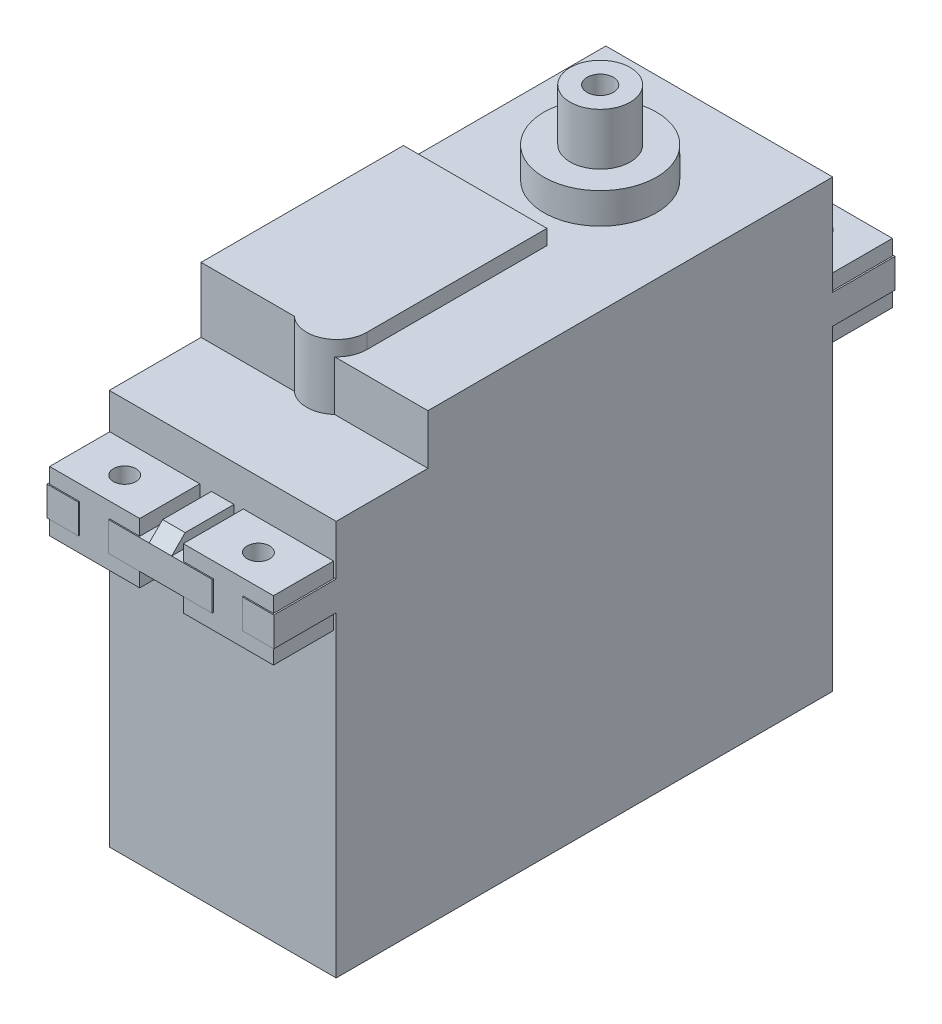
SolidWorks part; units mm, degrees
ref_plane "Front Plane" through (0, 0, 0) normal (0, 0, 1) x (1, 0, 0)
ref_plane "Top Plane" through (0, 0, 0) normal (0, 1, 0) x (1, 0, 0)
ref_plane "Right Plane" through (0, 0, 0) normal (1, 0, 0) x (0, 0, -1)
sketch "Sketch1" plane through (0, 0, 0) normal (1, 0, 0) x (0, 0, -1)
  line L0 (0, 0) -> (66.1, 0)
  line L1 (66.1, 0) -> (66.1, 42.1)
  line L2 (66.1, 42.1) -> (74.4, 42.1)
  line L3 (74.4, 42.1) -> (74.4, 46)
  line L4 (74.4, 46) -> (66.1, 46)
  line L5 (66.1, 46) -> (66.1, 59.3)
  line L6 (66.1, 59.3) -> (12.2136, 59.3)
  line L7 (12.2136, 59.3) -> (12.2136, 52.65)
  line L8 (12.2136, 52.65) -> (0, 52.65)
  line L9 (0, 52.65) -> (0, 46)
  line L10 (0, 46) -> (-8.3, 46)
  line L11 (-8.3, 46) -> (-8.3, 42.1)
  line L12 (-8.3, 42.1) -> (0, 42.1)
  line L13 (0, 42.1) -> (0, 0)
  dimension "D1" = 13.3
extrude "Boss-Extrude1" add sketch "Sketch1" along normal blind 30.2
sketch "Sketch9" plane through (0, 46, 0) normal (0, 1, 0) x (1, 0, 0)
  line L0 (15.1, 74.4) -> (15.1, -8.3) construction
  line L1 (30.2, 74.4) -> (0, 74.4) construction
  line L2 (30.2, -8.3) -> (0, -8.3) construction
  line L4 (22, 74.4) -> (22, 72.1375)
  line L5 (6.2, 74.4) -> (4.2, 74.4)
  line L6 (4.2, 74.4) -> (4.2, 72.1375)
  line L7 (6.2, 74.4) -> (8.2, 74.4)
  line L8 (8.2, 74.4) -> (8.2, 72.1375)
  line L9 (24, 74.4) -> (22, 74.4)
  line L10 (26, 74.4) -> (26, 72.1375)
  line L11 (24, 74.4) -> (26, 74.4)
  line L12 (0, 74.4) -> (0, 33.05) construction
  line L13 (0, 66.1) -> (0, 12.2136) construction
  line L14 (0, 33.05) -> (30.2, 33.05) construction
  line L15 (30.2, 66.1) -> (30.2, 12.2136) construction
  line L17 (24, -8.3) -> (26, -8.3)
  line L18 (26, -8.3) -> (26, -6.0375)
  line L19 (24, -8.3) -> (22, -8.3)
  line L20 (8.2, -8.3) -> (8.2, -6.0375)
  line L21 (6.2, -8.3) -> (8.2, -8.3)
  line L22 (4.2, -8.3) -> (4.2, -6.0375)
  line L23 (6.2, -8.3) -> (4.2, -8.3)
  line L24 (22, -8.3) -> (22, -6.0375)
  arc A0 (4.2, 72.1375) -> (8.2, 72.1375) centre (6.2, 70.25) ccw
  arc A1 (26, 72.1375) -> (22, 72.1375) centre (24, 70.25) cw
  arc A2 (26, -6.0375) -> (22, -6.0375) centre (24, -4.15) ccw
  arc A3 (4.2, -6.0375) -> (8.2, -6.0375) centre (6.2, -4.15) cw
extrude "Cut-Extrude3" cut sketch "Sketch9" against normal blind 6.9
sketch "Sketch10" plane through (0, 59.3, 0) normal (0, 1, 0) x (1, 0, 0)
  line L0 (6.2, 70.25) -> (6.2, 50.25) construction
  line L1 (6.2, 50.25) -> (17.2217, 50.25) construction
  line L2 (15.1, 74.4) -> (15.1, 50.25) construction
  line L3 (22, 74.4) -> (8.2, 74.4) construction
  circle A0 centre (15.1, 50.25) radius 7.5
extrude "Boss-Extrude6" add sketch "Sketch10" along normal blind 4.1
sketch "Sketch11" plane through (0, 63.4, 0) normal (0, 1, 0) x (1, 0, 0)
  circle A0 centre (15.1, 50.25) radius 4
  dimension "D1" = 8
extrude "Boss-Extrude7" add sketch "Sketch11" along normal blind 6.9
ref_plane "Plane3" through (0, 61.3, 0) normal (0, 1, 0) x (1, 0, 0)
sketch "Sketch14" plane through (0, 61.3, 0) normal (0, 1, 0) x (1, 0, 0)
  line L0 (0, 39.1568) -> (15.1, 39.1568)
  line L1 (0, 66.1) -> (0, 12.2136) construction
  line L2 (15.1, 39.1568) -> (19.1, 39.1568)
  line L3 (19.1, 39.1568) -> (19.1, 15.1789)
  line L5 (11.1, 15.1789) -> (0, 15.1789)
  line L6 (0, 15.1789) -> (0, 39.1568)
  arc A0 (11.1, 15.1789) -> (19.1, 15.1789) centre (15.1, 15.1789) ccw
extrude "Boss-Extrude8" add sketch "Sketch14" against normal blind 8.9
sketch "Sketch17" plane through (0, 59.3, 0) normal (0, 1, 0) x (1, 0, 0)
  line L0 (0, 12.2136) -> (15.1537, 12.2136)
  line L1 (15.1537, 12.2136) -> (15.1, 15.1789)
  line L2 (15.1, 15.1789) -> (0, 15.1789)
  line L3 (0, 15.1789) -> (0, 12.2136)
extrude "Boss-Extrude9" add sketch "Sketch17" along normal blind 2
sketch "Sketch18" plane through (0, 46, 0) normal (0, 1, 0) x (1, 0, 0)
  line L0 (15.1, 74.4) -> (16.6, 74.4)
  line L1 (22, 74.4) -> (8.2, 74.4) construction
  line L2 (16.6, 74.4) -> (16.6, 66.1)
  line L3 (30.2, 66.1) -> (0, 66.1) construction
  line L4 (16.6, 66.1) -> (13.6, 66.1)
  line L5 (13.6, 66.1) -> (13.6, 74.4)
  line L6 (13.6, 74.4) -> (15.1, 74.4)
  line L7 (0, 74.4) -> (0, 33.05) construction
  line L8 (0, 33.05) -> (30.2, 33.05) construction
  line L9 (30.2, 66.1) -> (30.2, 12.2136) construction
  line L10 (13.6, -8.3) -> (15.1, -8.3)
  line L11 (13.6, 0) -> (13.6, -8.3)
  line L12 (16.6, 0) -> (13.6, 0)
  line L13 (16.6, -8.3) -> (16.6, 0)
  line L14 (15.1, -8.3) -> (16.6, -8.3)
extrude "Boss-Extrude10" add sketch "Sketch18" along normal blind 1.8
sketch "Sketch22" plane through (16.6, 0, 0) normal (1, 0, 0) x (0, 0, -1)
  line L0 (74.4, 46) -> (72.6, 47.8)
  line L1 (66.1, 47.8) -> (74.4, 47.8) construction
  line L2 (72.6, 47.8) -> (74.4, 47.8)
  line L3 (74.4, 47.8) -> (74.4, 46)
  line L4 (33.05, 0) -> (33.05, 55.6135) construction
  line L5 (0, 0) -> (66.1, 0) construction
  line L6 (-8.3, 47.8) -> (-8.3, 46)
  line L7 (-6.5, 47.8) -> (-8.3, 47.8)
  line L8 (-8.3, 46) -> (-6.5, 47.8)
extrude "Cut-Extrude5" cut sketch "Sketch22" against normal blind 4
sketch "Sketch23" plane through (0, 70.3, 0) normal (0, 1, 0) x (1, 0, 0)
  circle A0 centre (15.1, 50.25) radius 1.75
  dimension "D1" = 3.5
extrude "Cut-Extrude6" cut sketch "Sketch23" against normal blind 7
sketch "Esquisse1" plane through (0, 0, -66.1) normal (0, 0, -1) x (-1, 0, 0)
  line L1 (-18.6, 7) -> (-11.6, 7)
  line L2 (-18.6, 7) -> (-18.6, 3)
  line L3 (-18.6, 3) -> (-11.6, 3)
  line L4 (-11.6, 7) -> (-11.6, 3)
  line L5 (-15.1, 0) -> (-15.1, 3) construction
  line L6 (-30.2, 0) -> (0, 0) construction
  dimension "D1" = 3
  dimension "D2" = 4
  dimension "D3" = 7
extrude "Boss.-Extru.1" add sketch "Esquisse1" along normal blind 7 draft 5
sketch "Esquisse2" plane through (0, 46, 0) normal (0, 1, 0) x (1, 0, 0)
  line L0 (15.1, -8.15) -> (15.1, 33.05) construction
  line L1 (12.2, -0.15) -> (0.2, -0.15)
  line L2 (12.2, -0.15) -> (12.2, -8.15)
  line L3 (12.2, -8.15) -> (0.2, -8.15)
  line L4 (0.2, -0.15) -> (0.2, -8.15)
  line L5 (12.2, -0.15) -> (0.2, -8.15) construction
  line L6 (12.2, -8.15) -> (0.2, -0.15) construction
  line L7 (15.1, 33.05) -> (0.2, 33.05) construction
  line L8 (18, -0.15) -> (18, -8.15)
  line L9 (18, -8.15) -> (30, -8.15)
  line L10 (30, -0.15) -> (30, -8.15)
  line L11 (18, -0.15) -> (30, -0.15)
  line L12 (18, 66.25) -> (30, 66.25)
  line L13 (30, 66.25) -> (30, 74.25)
  line L14 (18, 74.25) -> (30, 74.25)
  line L15 (18, 66.25) -> (18, 74.25)
  line L16 (0.2, 66.25) -> (0.2, 74.25)
  line L17 (12.2, 74.25) -> (0.2, 74.25)
  line L18 (12.2, 66.25) -> (12.2, 74.25)
  line L19 (12.2, 66.25) -> (0.2, 66.25)
  circle A0 centre (6.2, -4.15) radius 1.5
  circle A1 centre (24, -4.15) radius 1.5
  circle A2 centre (24, 70.25) radius 1.5
  circle A3 centre (6.2, 70.25) radius 1.5
  arc A4 (8.2, -6.0375) -> (4.2, -6.0375) centre (6.2, -4.15) ccw construction
  arc A5 (22, 72.1375) -> (26, 72.1375) centre (24, 70.25) ccw construction
  point P0 (6.2, -4.15)
  dimension "D1" = 12
  dimension "D3" = 3
  dimension "D2" = 8
extrude "Boss.-Extru.2" add sketch "Esquisse2" against normal blind 8 from offset 2.05 separate body
